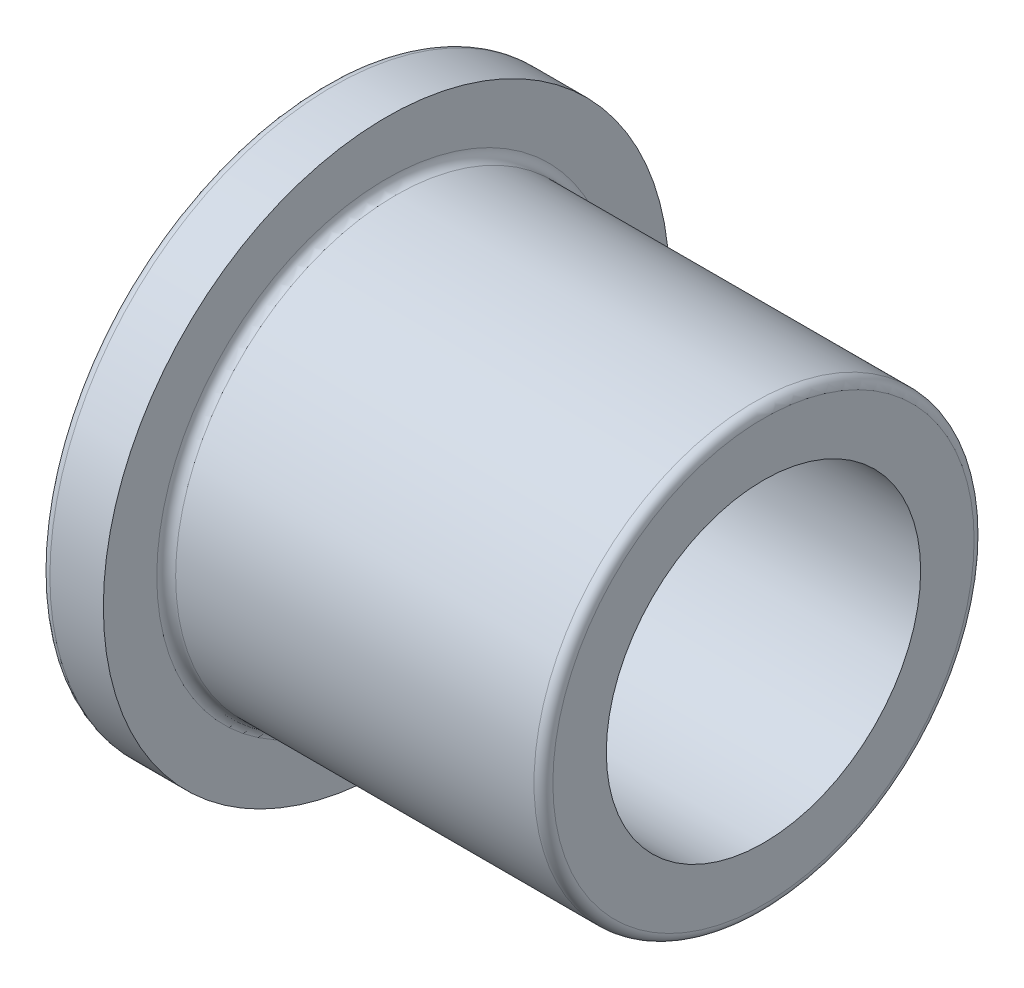
SolidWorks part; units mm, degrees
ref_plane "Front Plane" through (0, 0, 0) normal (0, 0, 1) x (1, 0, 0)
ref_plane "Top Plane" through (0, 0, 0) normal (0, 1, 0) x (1, 0, 0)
ref_plane "Right Plane" through (0, 0, 0) normal (1, 0, 0) x (0, 0, -1)
sketch "Sketch1" plane through (0, 0, 0) normal (1, 0, 0) x (0, 0, -1)
  circle A0 centre (0, 0) radius 7
  circle A1 centre (0, 0) radius 5
  dimension "D1" = 14
  dimension "D2" = 10
extrude "Boss-Extrude1" add sketch "Sketch1" against normal blind 12
sketch "Sketch2" plane through (-12, 0, 0) normal (-1, 0, 0) x (0, 0, 1)
  circle A0 centre (0, 0) radius 5 construction
  circle A1 centre (0, 0) radius 5
  circle A2 centre (0, 0) radius 9
  dimension "D1" = 18
extrude "Boss-Extrude2" add sketch "Sketch2" along normal blind 2
fillet "Fillet1" radius 0.3 3 edges at (-14, 0, 9) (0, 0, -7) (-12, 0, -7)
